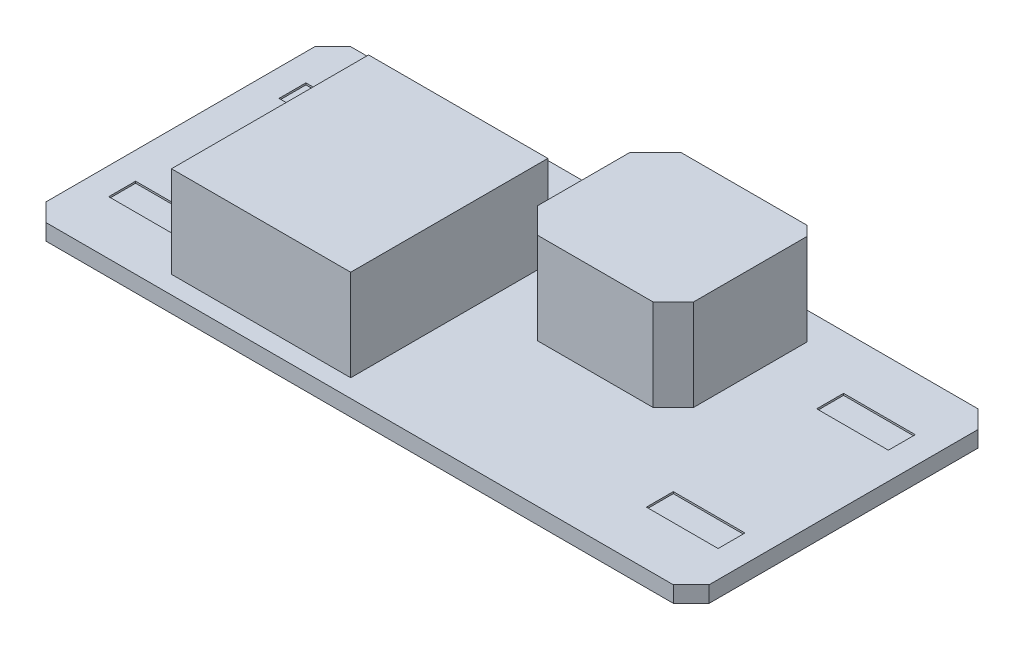
SolidWorks part; units mm, degrees
ref_plane "Plano frontal" through (0, 0, 0) normal (0, 0, 1) x (1, 0, 0)
ref_plane "Plano superior" through (0, 0, 0) normal (0, 1, 0) x (1, 0, 0)
ref_plane "Plano direito" through (0, 0, 0) normal (1, 0, 0) x (0, 0, -1)
sketch "Esboço1" plane through (0, 0, 0) normal (0, 1, 0) x (1, 0, 0)
  line L1 (18.5, 8.5) -> (-18.5, 8.5)
  line L2 (18.5, 8.5) -> (18.5, -8.5)
  line L3 (18.5, -8.5) -> (-18.5, -8.5)
  line L4 (-18.5, 8.5) -> (-18.5, -8.5)
  line L5 (18.5, 8.5) -> (-18.5, -8.5) construction
  line L6 (18.5, -8.5) -> (-18.5, 8.5) construction
  point P0 (0, 0)
  dimension "D1" = 37
  dimension "D2" = 17
extrude "Ressalto-extrusão1" add sketch "Esboço1" along normal mid plane 0.9
sketch "Esboço2" plane through (0, 0.45, 0) normal (0, 1, 0) x (1, 0, 0)
  line L0 (-18.5, -8.5) -> (18.5, -8.5) construction
  line L1 (-1.5, -7.5) -> (-11.5, -7.5)
  line L2 (-1.5, -7.5) -> (-1.5, 3.5)
  line L3 (-1.5, 3.5) -> (-11.5, 3.5)
  line L4 (-11.5, -7.5) -> (-11.5, 3.5)
  line L5 (-18.5, 8.5) -> (-18.5, -8.5) construction
  dimension "D1" = 1
  dimension "D2" = 17
  dimension "D3" = 12
  dimension "D4" = 10
extrude "Ressalto-extrusão2" add sketch "Esboço2" along normal blind 5.1
sketch "Esboço3" plane through (0, 0.45, 0) normal (0, 1, 0) x (1, 0, 0)
  line L0 (0.5, 0.9108) -> (0.5, 6.0892)
  line L1 (0.5, 6.0892) -> (1.9108, 7.5)
  line L2 (1.9108, 7.5) -> (8.9679, 7.5)
  line L3 (8.9679, 7.5) -> (9.5, 6.9679)
  line L4 (9.5, 6.9679) -> (9.5, 0.6204)
  line L5 (9.5, 0.6204) -> (8.3796, -0.5)
  line L6 (8.3796, -0.5) -> (1.9108, -0.5)
  line L7 (-1.5, -7.5) -> (-1.5, 3.5) construction
  line L8 (18.5, 8.5) -> (-18.5, 8.5) construction
  line L9 (0.5, 0.9108) -> (1.9108, -0.5)
  point P0 (5.4394, 7.5)
  point P11 (0, 0)
  point P14 (1.9108, -3.5)
  point P15 (0.5, -2.4218)
  point P16 (0.5, 0.5782)
  dimension "D1" = 2
  dimension "D2" = 1
  dimension "D3" = 135
  dimension "D4" = 135
  dimension "D5" = 9
  dimension "D6" = 8
  dimension "D7" = 135
  dimension "D8" = 6.5892
  dimension "D9" = 1.4108
  dimension "D10" = 0.5321
  dimension "D11" = 6.8796
extrude "Ressalto-extrusão3" add sketch "Esboço3" along normal blind 5.1
sketch "Esboço4" plane through (0, 0.45, 0) normal (0, 1, 0) x (1, 0, 0)
  line L0 (18.5, 8.5) -> (-18.5, 8.5) construction
  line L1 (-13, 5.5) -> (-17, 5.5)
  line L2 (-13, 5.5) -> (-13, 4)
  line L3 (-13, 4) -> (-17, 4)
  line L4 (-17, 5.5) -> (-17, 4)
  line L5 (-18.5, 8.5) -> (-18.5, -8.5) construction
  line L6 (-3.3, 0) -> (3.3, 0) construction
  line L7 (-17, -5.5) -> (-17, -4)
  line L8 (-13, -4) -> (-17, -4)
  line L9 (-13, -5.5) -> (-13, -4)
  line L10 (-13, -5.5) -> (-17, -5.5)
  line L11 (0, -3.3) -> (0, 3.3) construction
  line L12 (13, -5.5) -> (17, -5.5)
  line L13 (13, -5.5) -> (13, -4)
  line L14 (13, -4) -> (17, -4)
  line L15 (17, -5.5) -> (17, -4)
  line L16 (17, 5.5) -> (17, 4)
  line L17 (13, 4) -> (17, 4)
  line L18 (13, 5.5) -> (13, 4)
  line L19 (13, 5.5) -> (17, 5.5)
  dimension "D1" = 3
  dimension "D2" = 1.5
  dimension "D3" = 4
  dimension "D4" = 1.5
extrude "Corte-extrusão1" cut sketch "Esboço4" against normal blind 0.1
chamfer "Chanfro1" distance 1 angle 45 4 edges at (18.5, 0, 8.5) (18.5, 0, -8.5) (-18.5, 0, -8.5) (-18.5, 0, 8.5)
